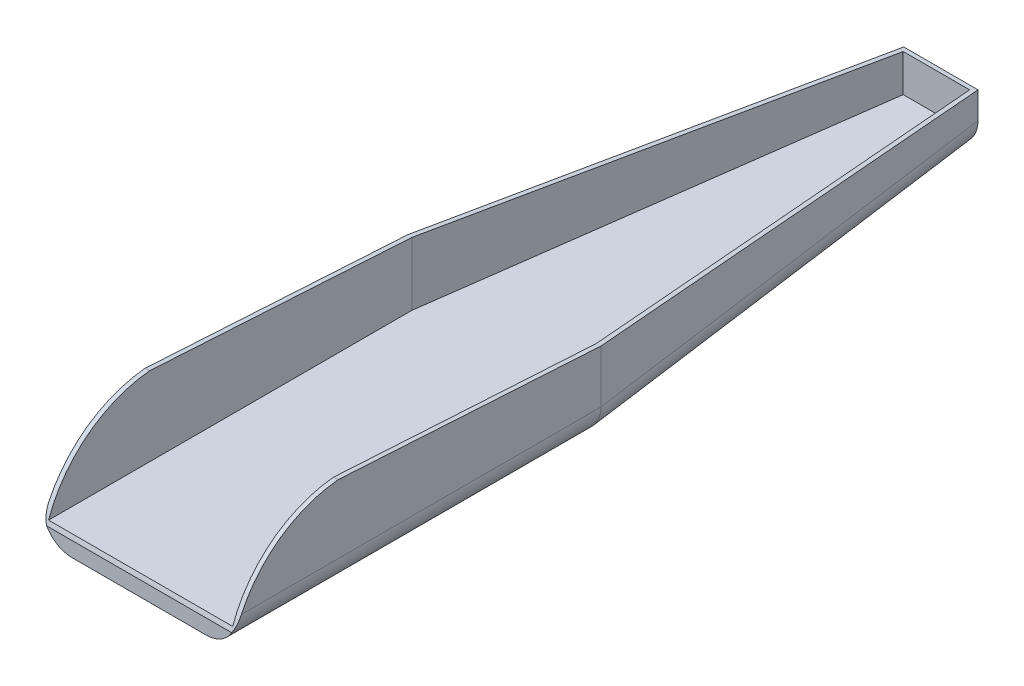
SolidWorks part; units mm, degrees
ref_plane "Front Plane" through (0, 0, 0) normal (0, 0, 1) x (1, 0, 0)
ref_plane "Top Plane" through (0, 0, 0) normal (0, 1, 0) x (1, 0, 0)
ref_plane "Right Plane" through (0, 0, 0) normal (1, 0, 0) x (0, 0, -1)
sketch "Sketch1" plane through (0, 0, 0) normal (1, 0, 0) x (0, 0, -1)
  line L0 (-101.2786, 0) -> (168.7214, 0)
  line L1 (168.7214, 0) -> (168.7214, 14)
  line L2 (168.7214, 14) -> (-66.7986, 28.0501)
  arc A0 (-101.2786, 0) -> (-66.7986, 28.0501) centre (-63.0506, -11.7739) cw
  dimension "D4" = 40
  dimension "D1" = 270
  dimension "D2" = 270
  dimension "D3" = 14
  dimension "D6" = 28.0501
extrude "Boss-Extrude1" add sketch "Sketch1" along normal blind 65
sketch "Sketch3" plane through (0, 0, 0) normal (0, -1, 0) x (1, 0, 0)
  line L0 (0, -21.7214) -> (20, -168.7214)
  line L2 (0, 101.2786) -> (0, -168.7214) construction
  line L5 (65, 101.2786) -> (0, 101.2786) construction
  line L6 (65, -168.7214) -> (0, -168.7214) construction
  dimension "D1" = 123
  dimension "D2" = 20
sketch "Sketch4" plane through (0, 0, 0) normal (0, -1, 0) x (-1, 0, 0)
  line L0 (-32.5, -101.2786) -> (-32.5, 183.2481) construction
  line L1 (-65, -101.2786) -> (0, -101.2786) construction
sketch "Sketch5" plane through (0, 0, 0) normal (0, -1, 0) x (1, 0, 0)
  line L0 (65, -21.7214) -> (45, -168.7214)
  line L1 (65, 101.2786) -> (65, -168.7214) construction
  line L2 (65, -168.7214) -> (0, -168.7214) construction
  dimension "D1" = 20
  dimension "D2" = 123
extrude "Cut-Extrude1" cut sketch "Sketch3" against normal through all and the other way through all flip side to cut contours L0
extrude "Cut-Extrude2" cut sketch "Sketch5" against normal through all and the other way through all contours L0
shell "Shell2" thickness 1.5
sketch "Sketch18" plane through (0, 0, 0) normal (0, -1, 0) x (1, 0, 0)
  line L0 (65, 101.2786) -> (0, 101.2786) construction
  line L1 (65, 101.2786) -> (65, -21.7214) construction
  line L2 (65, -21.7214) -> (45, -168.7214) construction
  line L3 (45, -168.7214) -> (20, -168.7214) construction
  line L4 (0, -21.7214) -> (20, -168.7214) construction
  line L5 (0, 101.2786) -> (0, -21.7214) construction
  line L6 (65, 101.2786) -> (0, 101.2786)
  line L7 (65, 101.2786) -> (65, -21.7214)
  line L8 (65, -21.7214) -> (45, -168.7214)
  line L9 (45, -168.7214) -> (20, -168.7214)
  line L10 (0, -21.7214) -> (20, -168.7214)
  line L11 (0, 101.2786) -> (0, -21.7214)
extrude "Boss-Extrude4" add sketch "Sketch18" along normal blind 5
fillet "Fillet12" radius 10 4 edges at (65, -5, 39.7786) (0, -5, 39.7786) (10, -5, -95.2214) (55, -5, -95.2214)
